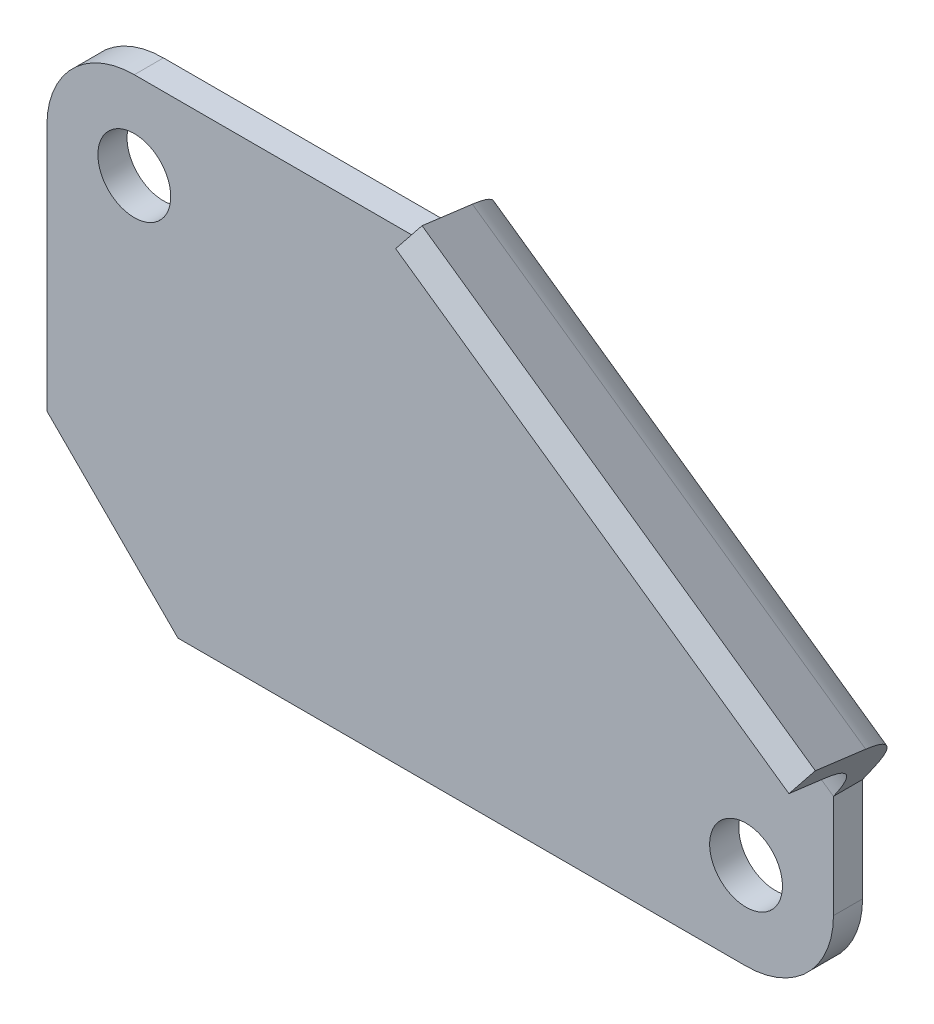
SolidWorks part; units mm, degrees
material "Manganese Bronze"
ref_plane "Front Plane" through (0, 0, 0) normal (0, 0, 1) x (1, 0, 0)
ref_plane "Top Plane" through (0, 0, 0) normal (0, 1, 0) x (1, 0, 0)
ref_plane "Right Plane" through (0, 0, 0) normal (1, 0, 0) x (0, 0, -1)
sketch "Sketch1" plane through (0, 0, 0) normal (0, 0, 1) x (1, 0, 0)
  line L0 (0, 0) -> (0, 34)
  line L1 (12, 46) -> (54, 46)
  line L2 (54, 46) -> (108, 8.1888)
  line L3 (108, 8.1888) -> (108, -6)
  line L5 (96, -18) -> (18, -18)
  line L6 (18, -18) -> (0, 0)
  arc A0 (108, -6) -> (96, -18) centre (96, -6) cw
  arc A1 (0, 34) -> (12, 46) centre (12, 34) cw
  circle A2 centre (12, 34) radius 5
  circle A3 centre (96, -6) radius 5
  point P9 (108, -18)
  point P12 (0, 46)
  dimension "D7" = 12
  dimension "D8" = 10
  dimension "D9" = 10
  dimension "D1" = 18
  dimension "D2" = 18
  dimension "D3" = 108
  dimension "D4" = 54
  dimension "D5" = 35
  dimension "D6" = 64
extrude "Boss-Extrude1" add sketch "Sketch1" along normal blind 4
ref_plane "Plane1" through (68.6216, -48.0494, 0) normal (0.8192, -0.5736, 0) x (0, 0, -1)
sketch "Sketch5" plane through (68.6216, -48.0494, 0) normal (0.8192, -0.5736, 0) x (0, 0, -1)
  line L0 (-4, 68.6541) -> (0, 68.6541)
  line L1 (0, 68.6541) -> (0, 79.4463)
  line L6 (0, 79.4463) -> (-16.5016, 86.1133)
  line L7 (-16.5016, 86.1133) -> (-18, 82.4046)
  line L8 (-18, 82.4046) -> (-11.5047, 79.7803)
  line L10 (-4, 68.6541) -> (-4, 86.2963) construction
  arc A1 (-11.5047, 79.7803) -> (-4, 68.6541) centre (-16, 68.6541) cw
  dimension "D4" = 14
  dimension "D2" = 12
  dimension "D1" = 4
  dimension "D3" = 112
extrude "Boss-Extrude2" add sketch "Sketch5" against normal up to vertex (44.4837 mm away)
fillet "Fillet1" radius 12 1 edges at (87.1901, 35.9348, 0)
